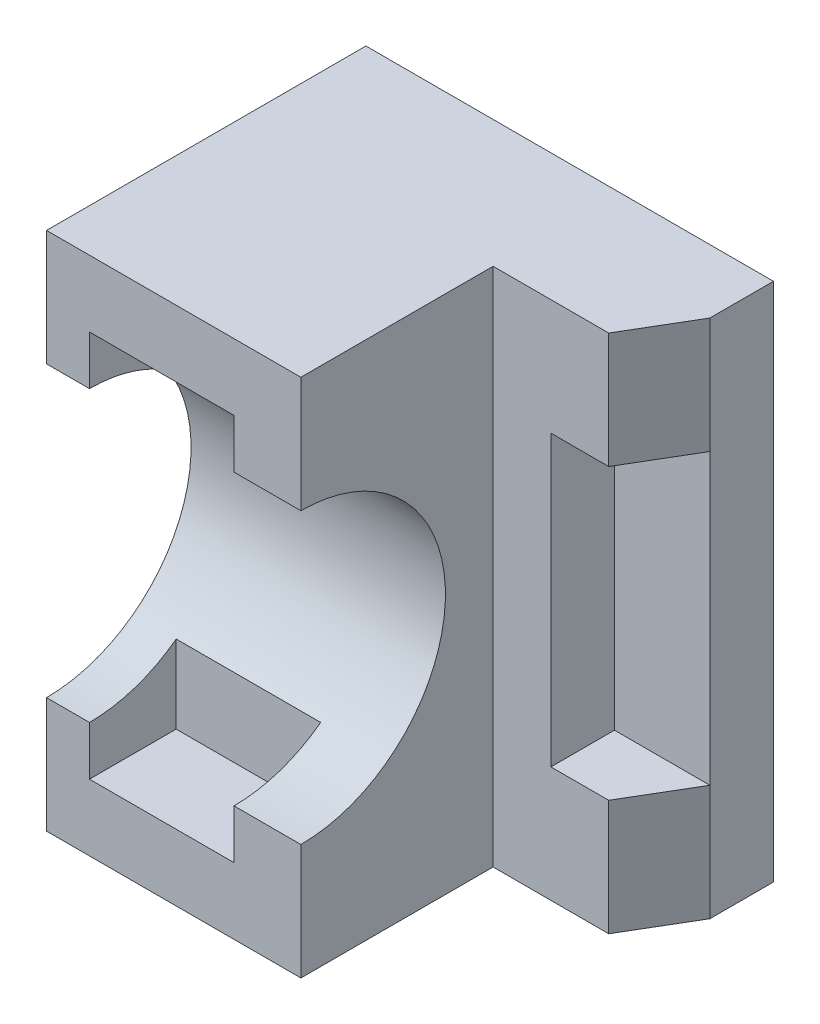
SolidWorks part; units mm, degrees
ref_plane "Front Plane" through (0, 0, 0) normal (0, 0, 1) x (1, 0, 0)
ref_plane "Top Plane" through (0, 0, 0) normal (0, 1, 0) x (1, 0, 0)
ref_plane "Right Plane" through (0, 0, 0) normal (1, 0, 0) x (0, 0, -1)
sketch "Sketch2" plane through (0, 0, 0) normal (0, 0, 1) x (1, 0, 0)
  line L1 (-35.25, 45) -> (35.25, 45)
  line L2 (-35.25, 45) -> (-35.25, -45)
  line L3 (-35.25, -45) -> (35.25, -45)
  line L4 (35.25, 45) -> (35.25, -45)
  line L5 (-35.25, 45) -> (35.25, -45) construction
  line L6 (-35.25, -45) -> (35.25, 45) construction
  point P0 (0, 0)
  dimension "D1" = 70.5
  dimension "D2" = 90
extrude "Boss-Extrude1" add sketch "Sketch2" along normal blind 55.25
sketch "Sketch4" plane through (0, -45, 0) normal (0, -1, 0) x (1, 0, 0)
  line L0 (8.75, 59.4763) -> (8.75, -6.8015) construction
  line L1 (-35.25, 55.25) -> (-35.25, 0) construction
  line L3 (35.25, 55.25) -> (35.25, 0) construction
  line L4 (35.25, 55.25) -> (35.25, 22)
  line L5 (8.75, 22) -> (8.75, 55.25)
  line L6 (8.75, 22) -> (28.75, 22)
  line L7 (28.75, 22) -> (35.25, 11)
  line L8 (-35.25, 55.25) -> (35.25, 55.25) construction
  line L9 (8.75, 55.25) -> (35.25, 55.25)
  line L10 (35.25, 22) -> (35.25, 11)
  dimension "D1" = 44
  dimension "D3" = 33.25
  dimension "D4" = 20
extrude "Cut-Extrude2" cut sketch "Sketch4" against normal through all
sketch "Sketch7" plane through (8.75, 0, 0) normal (1, 0, 0) x (0, 0, -1)
  line L0 (-70.4304, 0) -> (6.6193, 0) construction
  line L1 (-55.25, 45) -> (-55.25, -45) construction
  line L2 (-55.25, 25) -> (-55.25, -25)
  arc A0 (-55.25, 25) -> (-55.25, -25) centre (-55.25, 0) cw
  dimension "D1" = 25
extrude "Cut-Extrude3" cut sketch "Sketch7" against normal through all
sketch "Sketch8" plane through (0, 0, 55.25) normal (0, 0, 1) x (1, 0, 0)
  line L0 (8.75, 45) -> (-35.25, 45) construction
  line L1 (-27.8235, 33.5) -> (-2.8235, 33.5)
  line L2 (-27.8235, 33.5) -> (-27.8235, 18.5)
  line L3 (-27.8235, 18.5) -> (-2.8235, 18.5)
  line L4 (-2.8235, 33.5) -> (-2.8235, 18.5)
  line L5 (-27.8235, 33.5) -> (-2.8235, 18.5) construction
  line L6 (-27.8235, 18.5) -> (-2.8235, 33.5) construction
  line L7 (-48.1561, 0) -> (42.6716, 0) construction
  line L9 (-27.8235, -18.5) -> (-2.8235, -18.5)
  line L10 (-2.8235, -33.5) -> (-2.8235, -18.5)
  line L11 (-27.8235, -33.5) -> (-2.8235, -33.5)
  line L12 (-27.8235, -33.5) -> (-27.8235, -18.5)
  line L13 (8.75, 45) -> (8.75, 25) construction
  point P0 (-15.3235, 26)
  dimension "D1" = 25
  dimension "D2" = 15
  dimension "D3" = 11.5
  dimension "D4" = 11.5735
extrude "Cut-Extrude4" cut sketch "Sketch8" against normal blind 15
sketch "Sketch9" plane through (0, 0, 22) normal (0, 0, 1) x (1, 0, 0)
  line L0 (-41.3035, 0) -> (46.2682, 0) construction
  line L1 (46.2682, 0) -> (40.4761, 0)
  line L2 (35.25, 45) -> (35.25, -45) construction
  line L3 (18.75, 25) -> (35.25, 25)
  line L4 (18.75, 25) -> (18.75, -25)
  line L5 (18.75, -25) -> (35.25, -25)
  line L6 (35.25, 25) -> (35.25, -25)
  line L7 (18.75, 25) -> (35.25, -25) construction
  line L8 (18.75, -25) -> (35.25, 25) construction
  point P3 (27, 0)
  dimension "D1" = 16.5
  dimension "D2" = 50
  dimension "D3" = 5.2261
  dimension "D4" = 11.0182
extrude "Cut-Extrude5" cut sketch "Sketch9" against normal blind 11 contours L5 L6 L3 L4
